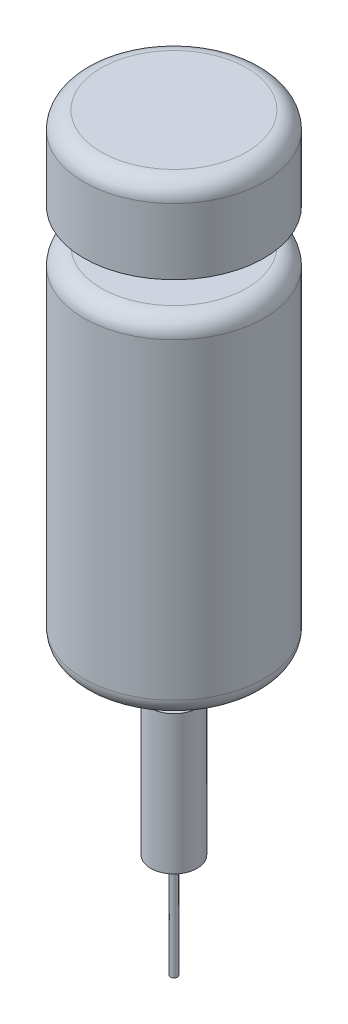
SolidWorks part; units mm, degrees
ref_plane "Front Plane" through (0, 0, 0) normal (0, 0, 1) x (1, 0, 0)
ref_plane "Top Plane" through (0, 0, 0) normal (0, 1, 0) x (1, 0, 0)
ref_plane "Right Plane" through (0, 0, 0) normal (1, 0, 0) x (0, 0, -1)
sketch "Sketch1" plane through (0, 0, 0) normal (0, 1, 0) x (1, 0, 0)
  circle A0 centre (0, 0) radius 26
  dimension "D1" = 52
extrude "Boss-Extrude2" add sketch "Sketch1" along normal blind 100
sketch "Sketch2" plane through (0, 100, 0) normal (0, 1, 0) x (1, 0, 0)
  circle A0 centre (0, 0) radius 7.5
  dimension "D1" = 15
extrude "Boss-Extrude4" add sketch "Sketch2" along normal blind 10
sketch "Sketch3" plane through (0, 110, 0) normal (0, 1, 0) x (1, 0, 0)
  circle A0 centre (0, 0) radius 26
  dimension "D1" = 52
extrude "Boss-Extrude5" add sketch "Sketch3" along normal blind 24
fillet "Fillet1" radius 5 1 edges at (0, 0, 26)
fillet "Fillet2" radius 5 1 edges at (0, 100, 26)
fillet "Fillet3" radius 5 1 edges at (0, 134, 26)
sketch "Sketch4" plane through (0, 0, 0) normal (0, -1, 0) x (1, 0, 0)
  circle A0 centre (0, 0) radius 10
extrude "Boss-Extrude6" add sketch "Sketch4" along normal blind 8
sketch "Sketch5" plane through (0, -8, 0) normal (0, -1, 0) x (1, 0, 0)
  circle A0 centre (0, 0) radius 2.9353
extrude "Boss-Extrude7" add sketch "Sketch5" along normal blind 4
sketch "Sketch6" plane through (0, -12, 0) normal (0, -1, 0) x (1, 0, 0)
  circle A0 centre (0, 0) radius 6.7
extrude "Boss-Extrude8" add sketch "Sketch6" along normal blind 40
sketch "Sketch7" plane through (0, -52, 0) normal (0, -1, 0) x (1, 0, 0)
  circle A0 centre (0, 0) radius 1
extrude "Boss-Extrude9" add sketch "Sketch7" along normal blind 30
